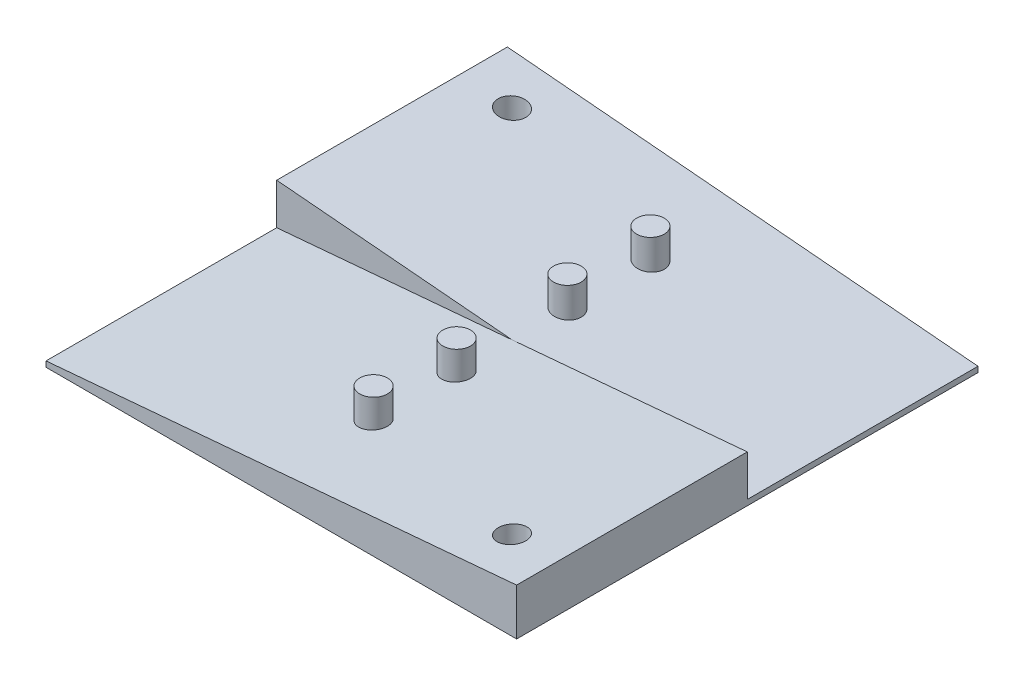
SolidWorks part; units mm, degrees
material "ABS"
ref_plane "Plano frontal" through (0, 0, 0) normal (0, 0, 1) x (1, 0, 0)
ref_plane "Plano superior" through (0, 0, 0) normal (0, 1, 0) x (1, 0, 0)
ref_plane "Plano direito" through (0, 0, 0) normal (1, 0, 0) x (0, 0, -1)
sketch "Esboço2" plane through (0, 0, 0) normal (0, 1, 0) x (1, 0, 0)
  line L7 (25.5, 25) -> (-25.5, 25)
  line L8 (25.5, 25) -> (25.5, -25)
  line L9 (25.5, -25) -> (-25.5, -25)
  line L10 (-25.5, 25) -> (-25.5, -25)
  line L11 (25.5, 25) -> (-25.5, -25) construction
  line L12 (25.5, -25) -> (-25.5, 25) construction
  point P0 (0, 0)
  dimension "D1" = 50
  dimension "D2" = 51
extrude "Ressalto-extrusão2" add sketch "Esboço2" along normal blind 6
sketch "Esboço3" plane through (0, 0, 25) normal (0, 0, 1) x (1, 0, 0)
  line L0 (-25.5, 0.6) -> (25.5, 5.0619)
  line L1 (25.5, 6) -> (25.5, 0) construction
  line L2 (-25.5, 6) -> (-25.5, 0) construction
  line L3 (-25.5, 0) -> (25.5, 0) construction
  line L4 (-25.5, 0.6) -> (-25.5, 6)
  line L5 (-25.5, 6) -> (25.5, 6)
  line L6 (25.5, 6) -> (25.5, 5.0619)
  dimension "D1" = 5
  dimension "D2" = 0.6
extrude "Corte-extrusão1" cut sketch "Esboço3" against normal blind 25
sketch "Esboço4" plane through (0, 0, -25) normal (0, 0, -1) x (-1, 0, 0)
  line L0 (-25.5, 0.6) -> (25.5, 5.0619)
  line L1 (-25.5, 6) -> (-25.5, 0) construction
  line L2 (25.5, 6) -> (25.5, 0) construction
  line L3 (-25.5, 0.6) -> (-25.5, 6)
  line L4 (-25.5, 6) -> (25.5, 6)
  line L5 (25.5, 6) -> (25.5, 5.0619)
  line L7 (-25.5, 0) -> (25.5, 0) construction
  dimension "D1" = 0.6
  dimension "D2" = 5
extrude "Corte-extrusão3" cut sketch "Esboço4" against normal blind 25
sketch "Esboço5" plane through (0, 0, 0) normal (0, -1, 0) x (1, 0, 0)
  line L0 (0, 6) -> (0, -6) construction
  circle A0 centre (0, 6) radius 1.5
  circle A1 centre (0, 15) radius 1.5
  circle A2 centre (0, -15) radius 1.5
  circle A3 centre (0, -6) radius 1.5
  point P12 (0, 0)
  dimension "D1" = 3
  dimension "D2" = 3
  dimension "D3" = 15
  dimension "D4" = 6
  dimension "D5" = 15
extrude "Ressalto-extrusão3" add sketch "Esboço5" against normal blind 6
sketch "Esboço8" plane through (0, 0, 0) normal (0, -1, 0) x (1, 0, 0)
  line L1 (20, 20) -> (-20, 20) construction
  line L2 (20, 20) -> (20, -20) construction
  line L3 (20, -20) -> (-20, -20) construction
  line L4 (-20, 20) -> (-20, -20) construction
  line L5 (20, 20) -> (-20, -20) construction
  line L6 (20, -20) -> (-20, 20) construction
  circle A1 centre (20, 20) radius 1.5
  circle A3 centre (-20, -20) radius 1.5
  point P8 (0, 0)
  dimension "D1" = 3
  dimension "D3" = 3
  dimension "D2" = 40
extrude "Corte-extrusão6" cut sketch "Esboço8" against normal through all
chamfer "Chanfro1" distance 1.5 angle 45 2 edges at (-20, 0, -21.5) (20, 0, 18.5)
equation "\"D5@Esboço5\"=\"D3@Esboço5\""
